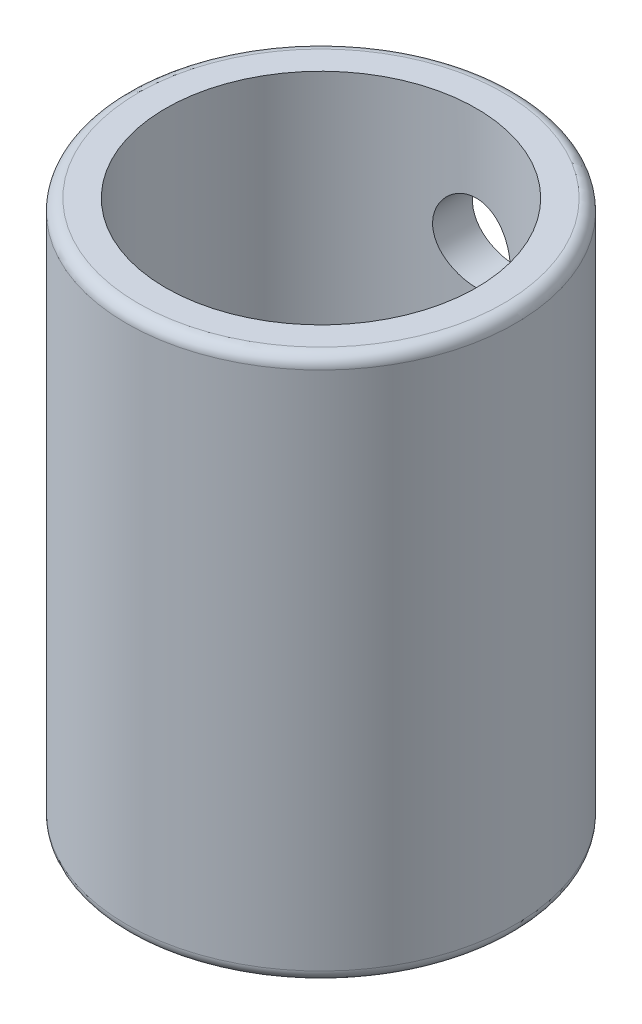
SolidWorks part; units mm, degrees
ref_plane "前视基准面" through (0, 0, 0) normal (0, 0, 1) x (1, 0, 0)
ref_plane "上视基准面" through (0, 0, 0) normal (0, 1, 0) x (1, 0, 0)
ref_plane "右视基准面" through (0, 0, 0) normal (1, 0, 0) x (0, 0, -1)
other "Configuration Table"
sketch "草图1" plane through (0, 0, 0) normal (0, 1, 0) x (1, 0, 0)
  circle A0 centre (0, 0) radius 2.5
  circle A1 centre (0, 0) radius 5
  dimension "D1" = 5
  dimension "D2" = 10
extrude "凸台-拉伸1" add sketch "草图1" along normal blind 7
sketch "草图2" plane through (0, 7, 0) normal (0, 1, 0) x (1, 0, 0)
  circle A0 centre (0, 0) radius 4
  circle A1 centre (0, 0) radius 5
  dimension "D1" = 8
  dimension "D2" = 10
extrude "凸台-拉伸2" add sketch "草图2" along normal blind 7
fillet "圆角1" radius 0.3 2 edges at (0, 0, 5) (0, 14, 5)
sketch "草图3" plane through (0, 0, 0) normal (0, 0, 1) x (1, 0, 0)
  line L0 (-4.7, 0) -> (4.7, 0) construction
  line L1 (4, 14) -> (-4, 14) construction
  circle A0 centre (0, 11) radius 1
  circle A1 centre (0, 3) radius 1
  dimension "D1" = 3
  dimension "D2" = 2
  dimension "D3" = 2
  dimension "D4" = 3
extrude "切除-拉伸1" cut sketch "草图3" against normal blind 7
